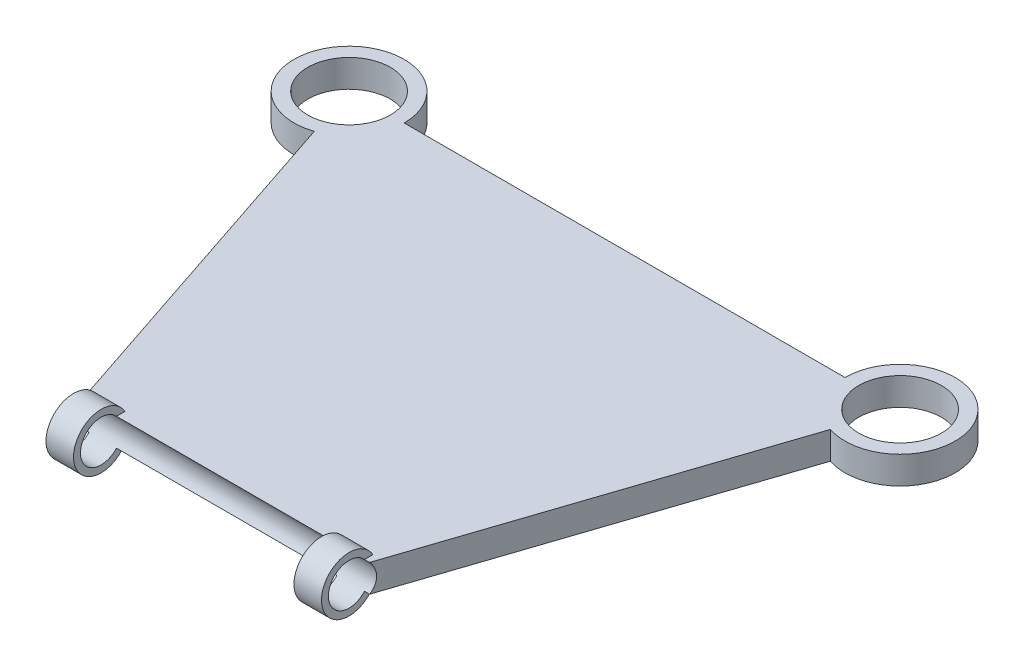
SolidWorks part; units mm, degrees
ref_plane "Front Plane" through (0, 0, 0) normal (0, 0, 1) x (1, 0, 0)
ref_plane "Top Plane" through (0, 0, 0) normal (0, 1, 0) x (1, 0, 0)
ref_plane "Right Plane" through (0, 0, 0) normal (1, 0, 0) x (0, 0, -1)
sketch "Sketch1" plane through (0, 0, 0) normal (0, 1, 0) x (1, 0, 0)
  line L0 (0, 0) -> (640, 0)
  line L1 (640, 0) -> (480, -480)
  line L2 (480, -480) -> (160, -480)
  line L3 (160, -480) -> (0, 0)
  circle A0 centre (0, 0) radius 64
  circle A1 centre (640, 0) radius 64
  circle A2 centre (0, 0) radius 48
  circle A3 centre (640, 0) radius 48
  dimension "D5" = 128
  dimension "D6" = 128
  dimension "D7" = 96
  dimension "D8" = 96
  dimension "D1" = 640
  dimension "D2" = 320
  dimension "D3" = 160
  dimension "D4" = 480
extrude "Boss-Extrude1" add sketch "Sketch1" along normal blind 32 contours A1 L0 A0 L3 L2 L1 | A2 L0 A0 L3 | A2 L3 A0 L0 | A3 L1 A1 L0 | A3 L0 A1 L1
ref_plane "Plane1" through (160, 0, 0) normal (-1, 0, 0) x (0, -1, 0)
ref_plane "Plane2" through (480, 0, 0) normal (-1, 0, 0) x (0, -1, 0)
sketch "Sketch2" plane through (160, 0, 0) normal (-1, 0, 0) x (0, -1, 0)
  line L0 (-32, 480) -> (0, 480) construction
  circle A0 centre (-16, 480) radius 32
  circle A1 centre (-16, 480) radius 24
  dimension "D1" = 64
  dimension "D2" = 48
extrude "Boss-Extrude2" add sketch "Sketch2" against normal blind 32
sketch "Sketch3" plane through (480, 0, 0) normal (-1, 0, 0) x (0, -1, 0)
  line L0 (-32, 480) -> (0, 480) construction
  circle A0 centre (-16, 480) radius 24
  circle A1 centre (-16, 480) radius 32
extrude "Boss-Extrude3" add sketch "Sketch3" along normal blind 32
sketch "Sketch4" plane through (160, 0, 0) normal (-1, 0, 0) x (0, -1, 0)
  line L0 (-32, 480) -> (0, 480) construction
  circle A0 centre (-16, 480) radius 24
extrude "Cut-Extrude1" cut sketch "Sketch4" against normal blind 689 and the other way blind 32
